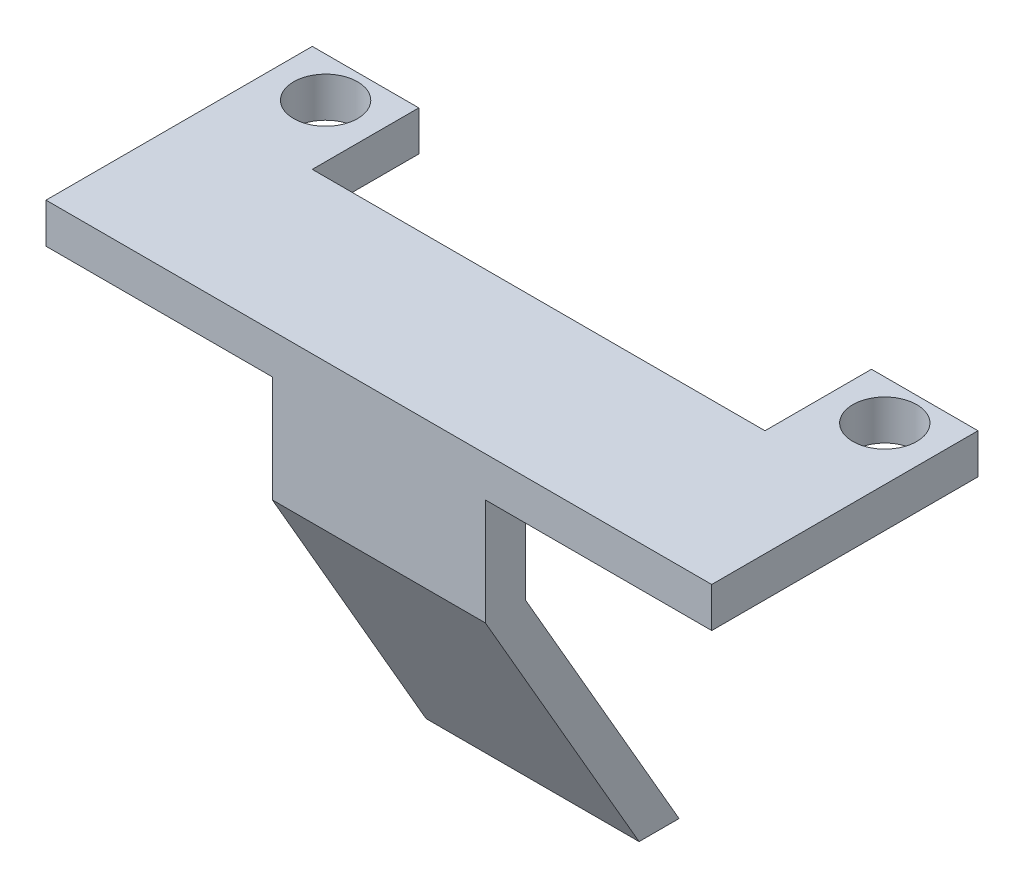
SolidWorks part; units mm, degrees
ref_plane "Front" through (0, 0, 0) normal (0, 0, 1) x (1, 0, 0)
ref_plane "Top" through (0, 0, 0) normal (0, 1, 0) x (1, 0, 0)
ref_plane "Right" through (0, 0, 0) normal (1, 0, 0) x (0, 0, -1)
sketch "Sketch1" plane through (0, 0, 0) normal (0, 1, 0) x (1, 0, 0)
  line L0 (-8.5, 0) -> (8.5, 0) construction
  line L1 (-8.5, 0) -> (-8.5, -4)
  line L2 (-8.5, -4) -> (8.5, -4)
  line L3 (8.5, -4) -> (8.5, 0)
  line L4 (8.5, 0) -> (12.5, 0)
  line L5 (12.5, 0) -> (12.5, -10)
  line L6 (12.5, -10) -> (-12.5, -10)
  line L7 (-12.5, -10) -> (-12.5, 0)
  line L8 (-12.5, 0) -> (-8.5, 0)
  line L9 (-10.5, 0) -> (-10.5, -1.5) construction
  line L10 (-10.5, -1.5) -> (10.5, -1.5) construction
  line L11 (10.5, -1.5) -> (10.5, 0) construction
  line L12 (-10.5, -1.5) -> (-12.5, -1.5) construction
  circle A0 centre (-10.5, -1.5) radius 1.2
  circle A1 centre (10.5, -1.5) radius 1.2
  point P4 (0, 0)
  dimension "D7" = 2.4
  dimension "D1" = 4
  dimension "D2" = 4
  dimension "D3" = 4
  dimension "D4" = 21
  dimension "D5" = 10
  dimension "D6" = 1.5
extrude "Boss-Extrude1" add sketch "Sketch1" along normal blind 1.5
sketch "Sketch2" plane through (0, 0, 0) normal (0, -1, 0) x (1, 0, 0)
  line L5 (-12.5, 10) -> (12.5, 10) construction
  line L6 (-4, 10) -> (4, 10)
  line L7 (-4, 10) -> (-4, 8.5)
  line L8 (-4, 8.5) -> (4, 8.5)
  line L9 (4, 10) -> (4, 8.5)
  line L10 (0, 0) -> (0, 10) construction
  point P10 (0, 0)
  dimension "D1" = 1.5
  dimension "D2" = 4
extrude "Boss-Extrude2" add sketch "Sketch2" along normal blind 4
sketch "Sketch3" plane through (-4, 0, 0) normal (-1, 0, 0) x (0, 0, 1)
  line L0 (10, -4) -> (4.2265, -14)
  line L1 (4.2265, -14) -> (2.7265, -14)
  line L2 (2.7265, -14) -> (8.5, -4)
  line L3 (8.5, -4) -> (10, -4)
  line L4 (10, -4) -> (10, 0) construction
  dimension "D1" = 1.5
  dimension "D2" = 210
  dimension "D3" = 10
extrude "Boss-Extrude3" add sketch "Sketch3" against normal up to surface (8 mm away) up to face at (4, -2, 9.25)
